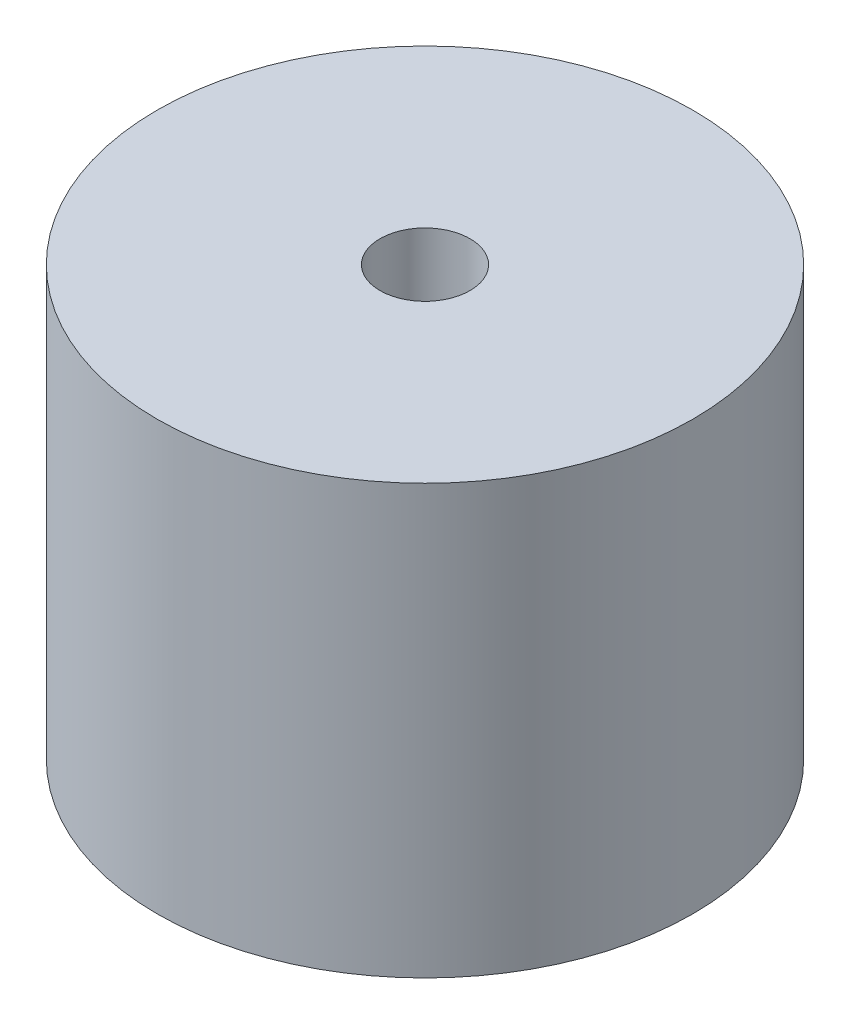
SolidWorks part; units mm, degrees
ref_plane "前视基准面" through (0, 0, 0) normal (0, 0, 1) x (1, 0, 0)
ref_plane "上视基准面" through (0, 0, 0) normal (0, 1, 0) x (1, 0, 0)
ref_plane "右视基准面" through (0, 0, 0) normal (1, 0, 0) x (0, 0, -1)
sketch "草图1" plane through (0, 0, 0) normal (0, 1, 0) x (1, 0, 0)
  circle A0 centre (0, 0) radius 12.5
  dimension "D1" = 25
extrude "凸台-拉伸1" add sketch "草图1" along normal blind 20
sketch "草图2" plane through (0, 0, 0) normal (0, -1, 0) x (1, 0, 0)
  circle A0 centre (0, 0) radius 10.5
  circle A1 centre (0, 0) radius 6
  circle A2 centre (0, 0) radius 12.5 construction
  dimension "D1" = 12
  dimension "D2" = 2
extrude "切除-拉伸1" cut sketch "草图2" against normal blind 1
sketch "草图3" plane through (0, 20, 0) normal (0, 1, 0) x (1, 0, 0)
  circle A0 centre (0, 0) radius 2.1
  dimension "D1" = 4.2
extrude "切除-拉伸2" cut sketch "草图3" against normal blind 10
